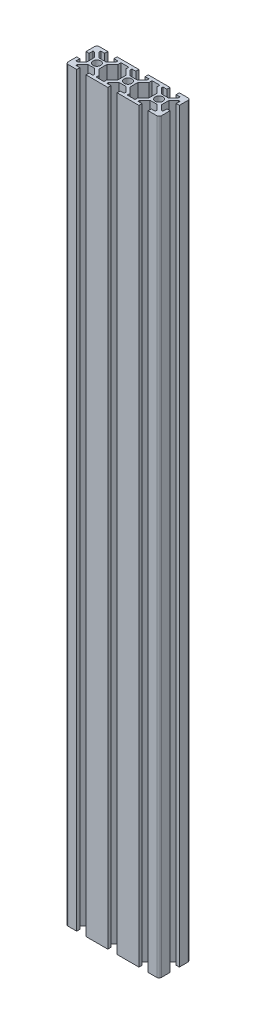
SolidWorks part; units mm, degrees
ref_plane "Front Plane" through (0, 0, 0) normal (0, 0, 1) x (1, 0, 0)
ref_plane "Top Plane" through (0, 0, 0) normal (0, 1, 0) x (1, 0, 0)
ref_plane "Right Plane" through (0, 0, 0) normal (1, 0, 0) x (0, 0, -1)
sketch "Sketch1" plane through (0, 0, 0) normal (0, 1, 0) x (1, 0, 0)
  line L0 (-20, 0) -> (20, 0) construction
  line L1 (0, 0) -> (0, 16.6338) construction
  line L2 (-2.1858, 3.6) -> (2.1858, 3.6)
  line L3 (2.1858, 3.6) -> (5.5, 6.9142)
  line L4 (5.5, 6.9142) -> (5.5, 8)
  line L5 (5.5, 8) -> (3, 8)
  line L6 (3, 8) -> (3, 10)
  line L7 (3, 10) -> (17, 10)
  line L8 (17, 10) -> (17, 8)
  line L9 (17, 8) -> (14.5, 8)
  line L10 (14.5, 8) -> (14.5, 6.9142)
  line L11 (14.5, 6.9142) -> (17.8142, 3.6)
  line L12 (17.8142, 3.6) -> (22.1858, 3.6)
  line L13 (22.1858, 3.6) -> (25.5, 6.9142)
  line L14 (25.5, 6.9142) -> (25.5, 8)
  line L15 (25.5, 8) -> (23, 8)
  line L16 (23, 8) -> (23, 10)
  line L17 (23, 10) -> (28.5, 10)
  line L18 (20, 0) -> (20, 3.6) construction
  line L19 (7.5, 8) -> (12.5, 8)
  line L20 (12.5, 8) -> (12.5, 6.0858)
  line L21 (12.5, 6.0858) -> (16.0858, 2.5)
  line L22 (3.9142, 2.5) -> (3.9142, -2.5)
  line L23 (7.5, 8) -> (7.5, 6.0858)
  line L24 (7.5, 6.0858) -> (3.9142, 2.5)
  line L25 (16.0858, 2.5) -> (16.0858, -2.5)
  line L26 (10, 10) -> (10, 8) construction
  line L27 (30, 8.5) -> (30, 3)
  line L28 (30, 3) -> (28, 3)
  line L29 (28, 3) -> (28, 5.5)
  line L30 (28, 5.5) -> (26.9142, 5.5)
  line L31 (26.9142, 5.5) -> (23.9142, 2.5)
  line L32 (23.9142, 2.5) -> (23.9142, -2.5)
  line L33 (20, 0) -> (24.5324, 0) construction
  line L34 (25.5, 6.9142) -> (26.9142, 5.5) construction
  line L35 (7.5, -6.0858) -> (3.9142, -2.5)
  line L36 (7.5, -8) -> (7.5, -6.0858)
  line L37 (7.5, -8) -> (12.5, -8)
  line L38 (12.5, -8) -> (12.5, -6.0858)
  line L39 (12.5, -6.0858) -> (16.0858, -2.5)
  line L40 (26.9142, -5.5) -> (23.9142, -2.5)
  line L41 (28, -5.5) -> (26.9142, -5.5)
  line L42 (28, -3) -> (28, -5.5)
  line L43 (30, -3) -> (28, -3)
  line L44 (30, -8.5) -> (30, -3)
  line L45 (23, -10) -> (28.5, -10)
  line L46 (23, -8) -> (23, -10)
  line L47 (25.5, -8) -> (23, -8)
  line L48 (25.5, -6.9142) -> (25.5, -8)
  line L49 (22.1858, -3.6) -> (25.5, -6.9142)
  line L50 (17.8142, -3.6) -> (22.1858, -3.6)
  line L51 (14.5, -6.9142) -> (17.8142, -3.6)
  line L52 (14.5, -8) -> (14.5, -6.9142)
  line L53 (17, -8) -> (14.5, -8)
  line L54 (17, -10) -> (17, -8)
  line L55 (3, -10) -> (17, -10)
  line L56 (3, -8) -> (3, -10)
  line L57 (5.5, -8) -> (3, -8)
  line L58 (5.5, -6.9142) -> (5.5, -8)
  line L59 (2.1858, -3.6) -> (5.5, -6.9142)
  line L60 (-2.1858, -3.6) -> (2.1858, -3.6)
  line L61 (-7.5, -6.0858) -> (-3.9142, -2.5)
  line L62 (-7.5, -8) -> (-7.5, -6.0858)
  line L63 (-7.5, -8) -> (-12.5, -8)
  line L64 (-12.5, -8) -> (-12.5, -6.0858)
  line L65 (-12.5, -6.0858) -> (-16.0858, -2.5)
  line L66 (-16.0858, 2.5) -> (-16.0858, -2.5)
  line L67 (-12.5, 6.0858) -> (-16.0858, 2.5)
  line L68 (-12.5, 8) -> (-12.5, 6.0858)
  line L69 (-7.5, 8) -> (-12.5, 8)
  line L70 (-7.5, 8) -> (-7.5, 6.0858)
  line L71 (-7.5, 6.0858) -> (-3.9142, 2.5)
  line L72 (-3.9142, 2.5) -> (-3.9142, -2.5)
  line L73 (-2.1858, -3.6) -> (-5.5, -6.9142)
  line L74 (-5.5, -6.9142) -> (-5.5, -8)
  line L75 (-5.5, -8) -> (-3, -8)
  line L76 (-3, -8) -> (-3, -10)
  line L77 (-3, -10) -> (-17, -10)
  line L78 (-17, -10) -> (-17, -8)
  line L79 (-17, -8) -> (-14.5, -8)
  line L80 (-14.5, -8) -> (-14.5, -6.9142)
  line L81 (-14.5, -6.9142) -> (-17.8142, -3.6)
  line L82 (-17.8142, -3.6) -> (-22.1858, -3.6)
  line L83 (-22.1858, -3.6) -> (-25.5, -6.9142)
  line L84 (-25.5, -6.9142) -> (-25.5, -8)
  line L85 (-25.5, -8) -> (-23, -8)
  line L86 (-23, -8) -> (-23, -10)
  line L87 (-23, -10) -> (-28.5, -10)
  line L88 (-30, -8.5) -> (-30, -3)
  line L89 (-30, -3) -> (-28, -3)
  line L90 (-28, -3) -> (-28, -5.5)
  line L91 (-28, -5.5) -> (-26.9142, -5.5)
  line L92 (-26.9142, -5.5) -> (-23.9142, -2.5)
  line L93 (-23.9142, 2.5) -> (-23.9142, -2.5)
  line L94 (-26.9142, 5.5) -> (-23.9142, 2.5)
  line L95 (-28, 5.5) -> (-26.9142, 5.5)
  line L96 (-28, 3) -> (-28, 5.5)
  line L97 (-30, 3) -> (-28, 3)
  line L98 (-30, 8.5) -> (-30, 3)
  line L99 (-23, 10) -> (-28.5, 10)
  line L100 (-23, 8) -> (-23, 10)
  line L101 (-25.5, 8) -> (-23, 8)
  line L102 (-25.5, 6.9142) -> (-25.5, 8)
  line L103 (-22.1858, 3.6) -> (-25.5, 6.9142)
  line L104 (-17.8142, 3.6) -> (-22.1858, 3.6)
  line L105 (-14.5, 6.9142) -> (-17.8142, 3.6)
  line L106 (-14.5, 8) -> (-14.5, 6.9142)
  line L107 (-17, 8) -> (-14.5, 8)
  line L108 (-17, 10) -> (-17, 8)
  line L109 (-3, 10) -> (-17, 10)
  line L110 (-3, 8) -> (-3, 10)
  line L111 (-5.5, 8) -> (-3, 8)
  line L112 (-5.5, 6.9142) -> (-5.5, 8)
  line L113 (-2.1858, 3.6) -> (-5.5, 6.9142)
  circle A0 centre (0, 0) radius 2.5
  circle A1 centre (20, 0) radius 2.5
  circle A2 centre (-20, 0) radius 2.5
  arc A3 (28.5, 10) -> (30, 8.5) centre (28.5, 8.5) cw
  arc A4 (28.5, -10) -> (30, -8.5) centre (28.5, -8.5) ccw
  arc A5 (-28.5, -10) -> (-30, -8.5) centre (-28.5, -8.5) cw
  arc A6 (-28.5, 10) -> (-30, 8.5) centre (-28.5, 8.5) ccw
  point P19 (0, 3.6)
  point P86 (0, -3.6)
  point P132 (0, 3.6)
  dimension "D3" = 2
  dimension "D1" = 5
  dimension "D7" = 3
  dimension "D13" = 1.5
  dimension "D2" = 20
  dimension "D4" = 6.4
  dimension "D5" = 45
  dimension "D6" = 10
  dimension "D8" = 6
  dimension "D9" = 11
  dimension "D10" = 2
  dimension "D11" = 2
  dimension "D12" = 2
  dimension "D14" = 3
  dimension "D15" = 2
  dimension "D16" = 30
extrude "Boss-Extrude1" add sketch "Sketch1" along normal mid plane 480
